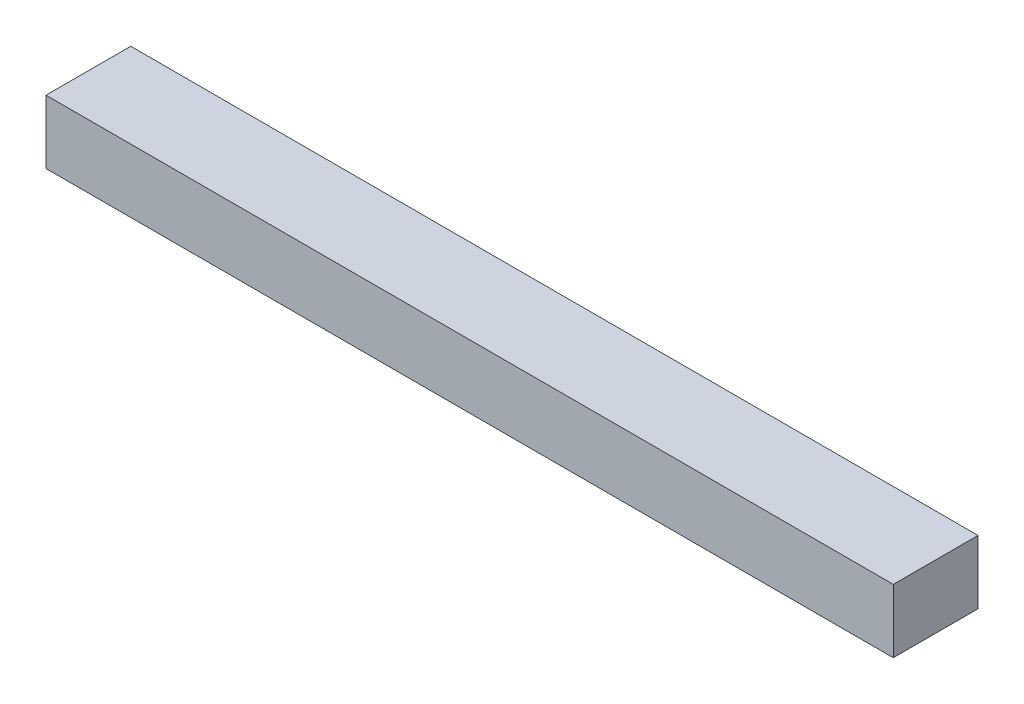
SolidWorks part; units mm, degrees
ref_plane "Front Plane" through (0, 0, 0) normal (0, 0, 1) x (1, 0, 0)
ref_plane "Top Plane" through (0, 0, 0) normal (0, 1, 0) x (1, 0, 0)
ref_plane "Right Plane" through (0, 0, 0) normal (1, 0, 0) x (0, 0, -1)
other "Configuration Table"
sketch "Sketch2" plane through (0, 0, 0) normal (0, 0, 1) x (1, 0, 0)
  line L1 (0, -3.0477) -> (10, -3.0477)
  line L2 (0, -3.0477) -> (0, -2.2977)
  line L3 (0, -2.2977) -> (10, -2.2977)
  line L4 (10, -3.0477) -> (10, -2.2977)
  dimension "D1" = 10
  dimension "D2" = 0.75
extrude "Extrude1" add sketch "Sketch2" along normal blind 1
